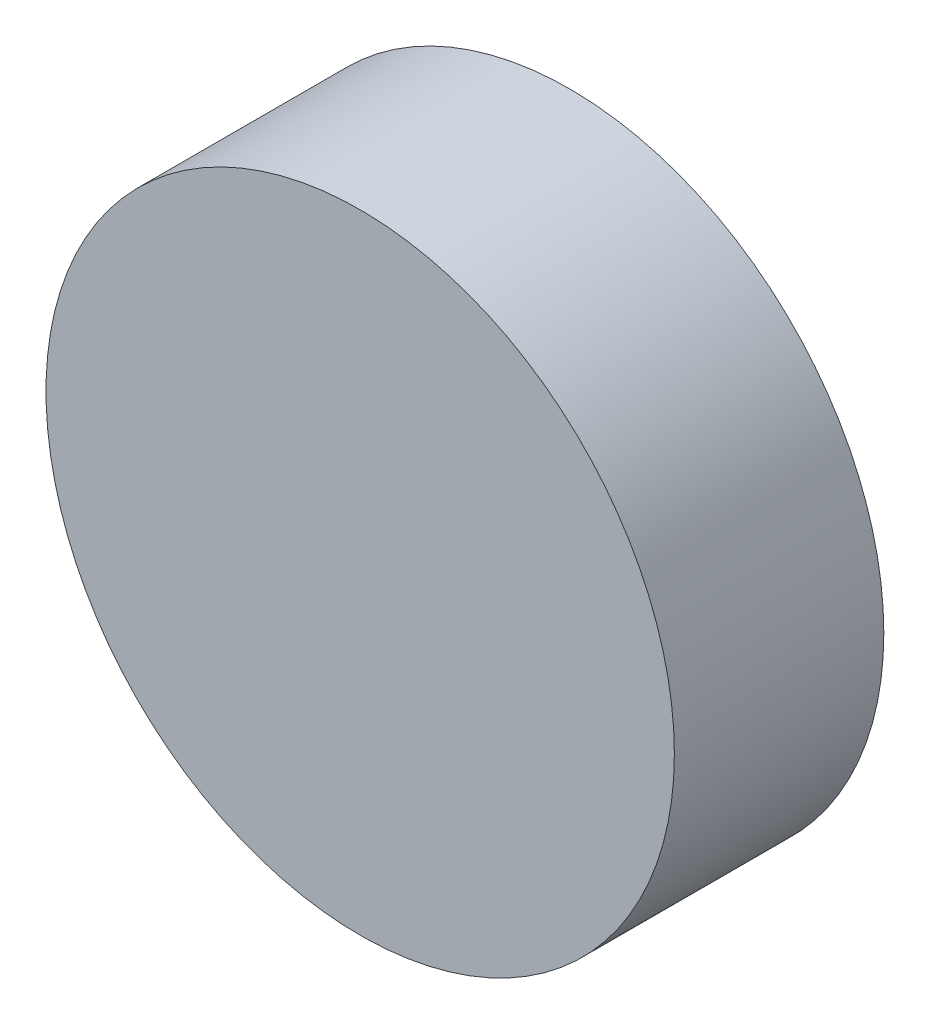
SolidWorks part; units mm, degrees
ref_plane "Front Plane" through (0, 0, 0) normal (0, 0, 1) x (1, 0, 0)
ref_plane "Top Plane" through (0, 0, 0) normal (0, 1, 0) x (1, 0, 0)
ref_plane "Right Plane" through (0, 0, 0) normal (1, 0, 0) x (0, 0, -1)
sketch "Sketch1" plane through (0, 0, 0) normal (0, 0, 1) x (1, 0, 0)
  circle A0 centre (0, 0) radius 1.5
  dimension "D1" = 3
extrude "Boss-Extrude1" add sketch "Sketch1" along normal blind 1
